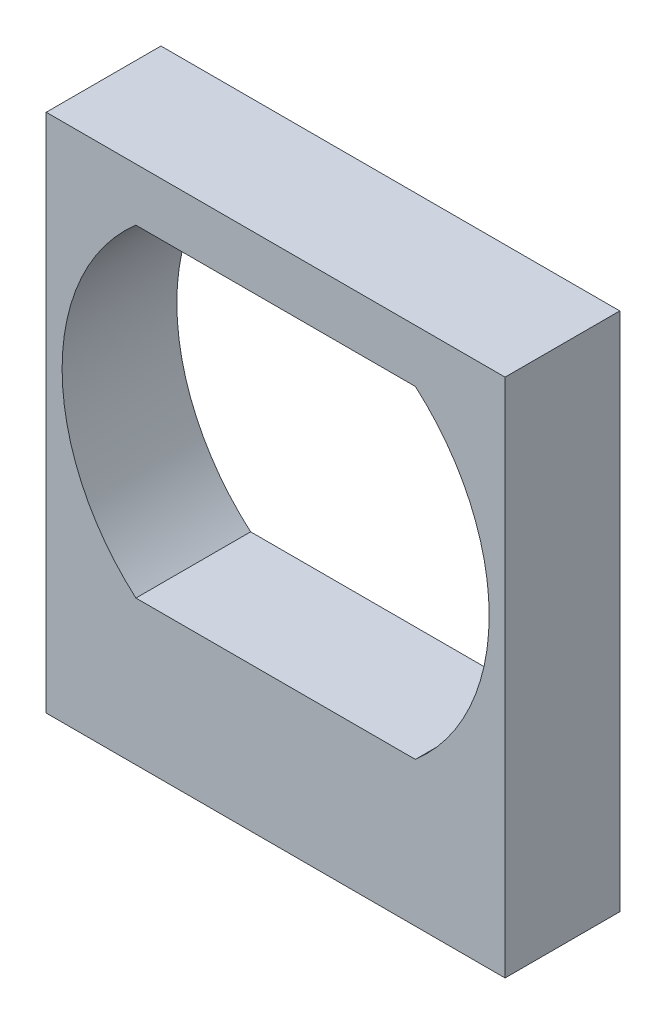
SolidWorks part; units mm, degrees
ref_plane "Front Plane" through (0, 0, 0) normal (1, 0, 0) x (0, 1, 0)
ref_plane "Top Plane" through (0, 0, 0) normal (0, 0, 1) x (0, 1, 0)
ref_plane "Right Plane" through (0, 0, 0) normal (0, 1, 0) x (-1, 0, 0)
sketch "Sketch1" plane through (0, 0, 0) normal (0, 0, 1) x (0, 1, 0)
  line L2 (-9.15, 7.9175) -> (-9.15, -7.9175)
  line L4 (9.15, 7.9175) -> (9.15, -7.9175)
  arc A0 (9.15, 7.9175) -> (-9.15, 7.9175) centre (0, 0) ccw
  arc A1 (-9.15, -7.9175) -> (9.15, -7.9175) centre (0, 0) ccw
  circle A2 centre (0, 0) radius 1.03 construction
  point P7 (9.15, 0)
  dimension "D3" = 24.2
  dimension "D2" = 2.06
  dimension "D1" = 18.3
sketch "Sketch2" plane through (0, 0, 0) normal (0, 0, 1) x (0, 1, 0)
  line L1 (-17.337, 13) -> (12.15, 13)
  line L2 (-17.337, 13) -> (-17.337, -13)
  line L3 (-17.337, -13) -> (12.15, -13)
  line L4 (12.15, 13) -> (12.15, -13)
  line L5 (9.15, 7.9175) -> (9.15, -7.9175) construction
  point P6 (12.15, 0)
  dimension "D1" = 26
  dimension "D2" = 3
  dimension "D3" = 17.337
extrude "Boss-Extrude1" add sketch "Sketch2" along normal blind 6.5
extrude "Cut-Extrude1" cut sketch "Sketch1" along normal through all
sketch "Sketch3" plane through (0, -17.337, 0) normal (0, -1, 0) x (1, 0, 0)
  line L0 (0, -3.575) -> (0, 3.575) construction
  line L1 (13, 6.5) -> (13, 0) construction
  circle A0 centre (0, 3.25) radius 1.5
  point P0 (0, 3.25)
  point P8 (13, 3.25)
  dimension "D1" = 3
hole_wizard "M2x0.4 Tapped Hole1" positions "Sketch3" profile "Sketch6" tap size "M2x0.4" standard "ANSI Metric"
sketch "Sketch6" plane through (0, -17.337, 3.25) normal (1, 0, 0) x (0, 0, -1)
  line L0 (0, 0) -> (0, 5.6807)
  line L1 (0, 5.6807) -> (0.8, 5.2)
  line L2 (0.8, 5.2) -> (0.8, 0)
  line L5 (0.8, 0) -> (0, 0)
  line L10 (0, 5.6807) -> (-0.8, 5.2) construction
  line L11 (0, -6.35) -> (0, 107.95) construction
  dimension "Tap Drill Dia." = 1.6
  dimension "Tap Drill Depth" = 5.2
  dimension "Drill Angle" = 118
cosmetic thread "Hole Thread1" parameters "D1"=4, "D2"=2
